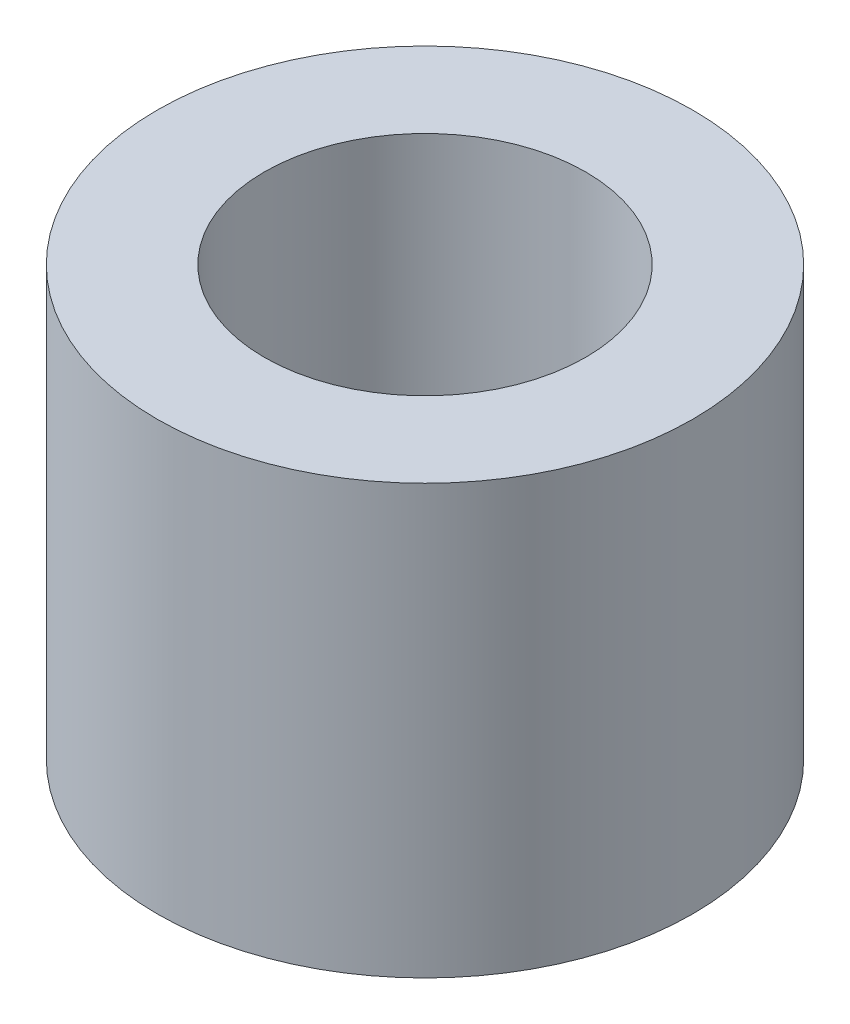
SolidWorks part; units mm, degrees
material "Brass"
ref_plane "Front Plane" through (0, 0, 0) normal (0, 0, 1) x (1, 0, 0)
ref_plane "Top Plane" through (0, 0, 0) normal (0, 1, 0) x (1, 0, 0)
ref_plane "Right Plane" through (0, 0, 0) normal (1, 0, 0) x (0, 0, -1)
sketch "Sketch1" plane through (0, 0, 0) normal (0, 1, 0) x (1, 0, 0)
  circle A0 centre (0, 0) radius 1.5
  circle A1 centre (0, 0) radius 2.5
  dimension "D1" = 3
  dimension "D2" = 5
extrude "Boss-Extrude1" add sketch "Sketch1" along normal blind 4
